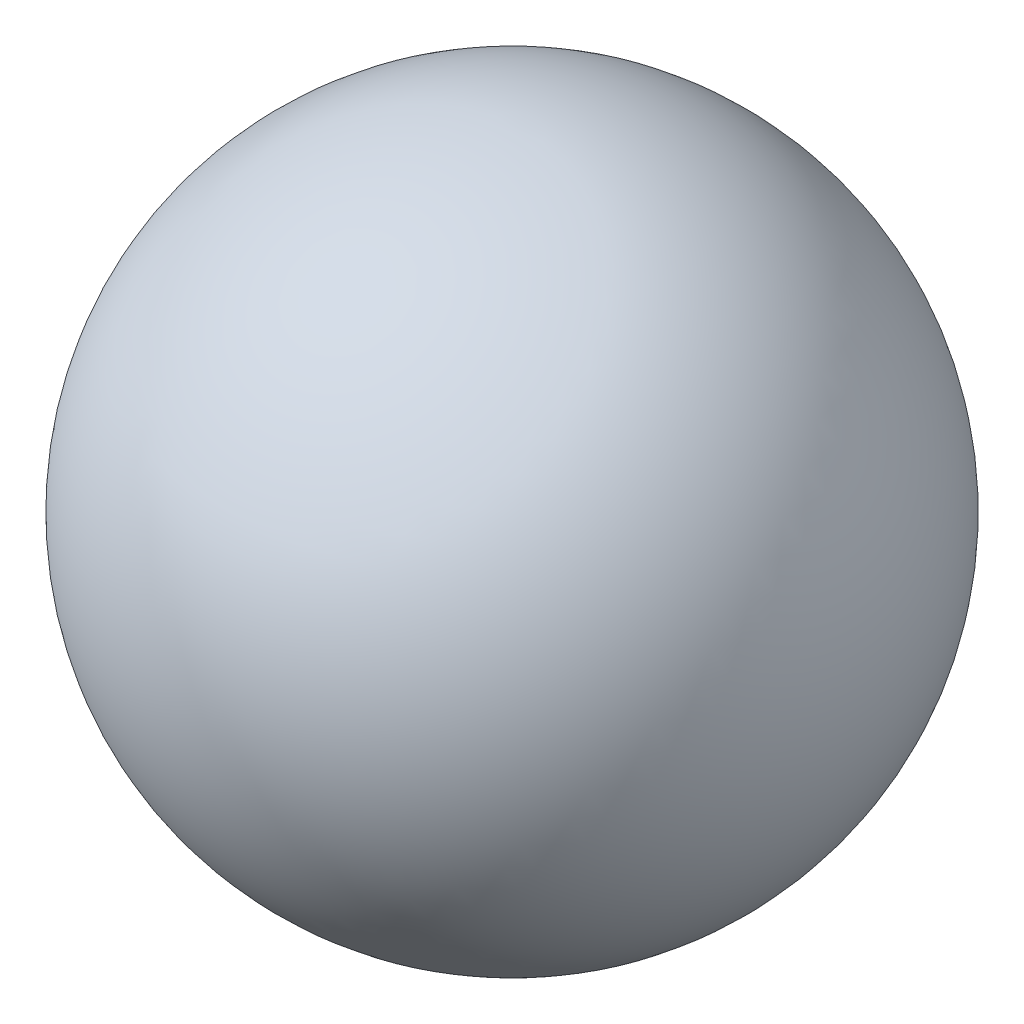
SolidWorks part; units mm, degrees
ref_plane "Front Plane" through (0, 0, 0) normal (0, 0, 1) x (1, 0, 0)
ref_plane "Top Plane" through (0, 0, 0) normal (0, 1, 0) x (1, 0, 0)
ref_plane "Right Plane" through (0, 0, 0) normal (1, 0, 0) x (0, 0, -1)
sketch "Sketch1" plane through (0, 0, 0) normal (0, 0, 1) x (1, 0, 0)
  line L0 (0, 155.575) -> (0, -155.575)
  arc A0 (0, 155.575) -> (0, -155.575) centre (0, 0) cw
  dimension "D1" = 311.15
revolve "Revolve1" add sketch "Sketch1" angle 360 about L0
